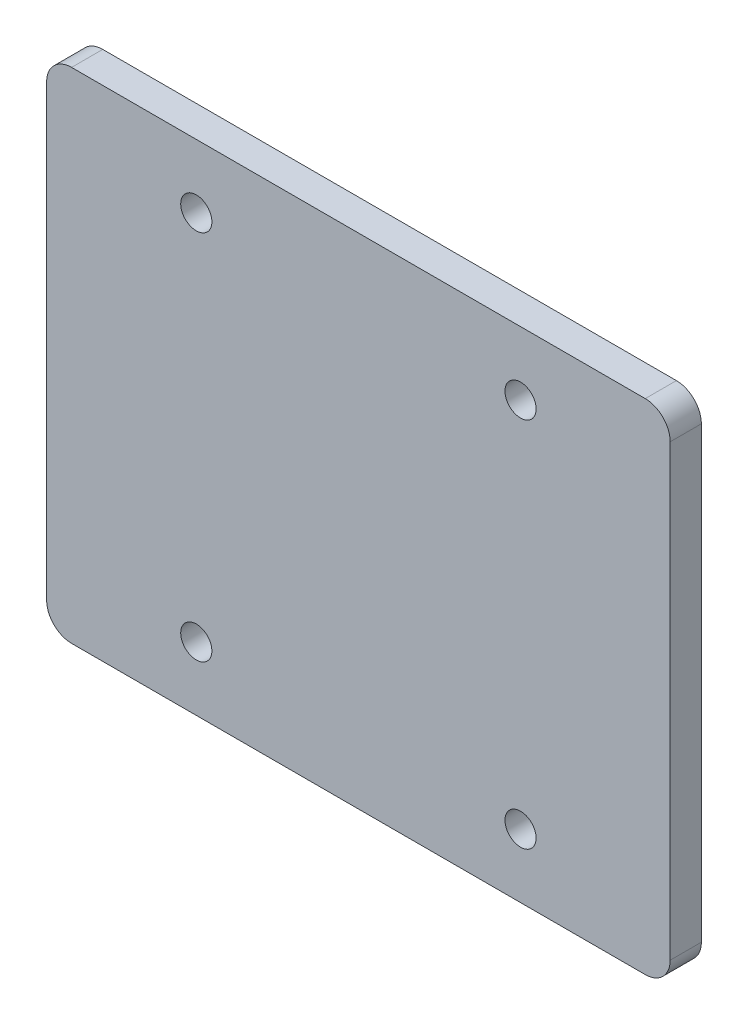
SolidWorks part; units mm, degrees
material "1060 Alloy"
ref_plane "Front Plane" through (0, 0, 0) normal (0, 0, 1) x (1, 0, 0)
ref_plane "Top Plane" through (0, 0, 0) normal (0, 1, 0) x (1, 0, 0)
ref_plane "Right Plane" through (0, 0, 0) normal (1, 0, 0) x (0, 0, -1)
sketch "Sketch1" plane through (0, 0, 0) normal (0, 0, 1) x (1, 0, 0)
  line L1 (0, 0) -> (63.5, 0)
  line L2 (0, 0) -> (0, 50.8)
  line L3 (0, 50.8) -> (63.5, 50.8)
  line L4 (63.5, 0) -> (63.5, 50.8)
  dimension "D1" = 63.5
  dimension "D2" = 50.8
extrude "Boss-Extrude1" add sketch "Sketch1" along normal blind 3.175
fillet "Fillet1" radius 2.54 4 edges at (0, 0, 1.5875) (63.5, 0, 1.5875) (0, 50.8, 1.5875) (63.5, 50.8, 1.5875)
sketch "Sketch2" plane through (0, 0, 3.175) normal (0, 0, 1) x (1, 0, 0)
  line L0 (31.75, 0) -> (31.75, 50.8)
  line L1 (2.54, 0) -> (60.96, 0) construction
  line L2 (60.96, 50.8) -> (2.54, 50.8) construction
  line L3 (63.5, 25.4) -> (0, 25.4)
  line L4 (63.5, 2.54) -> (63.5, 48.26) construction
  line L5 (0, 48.26) -> (0, 2.54) construction
sketch "Sketch3" plane through (0, 0, 0) normal (0, 0, -1) x (-1, 0, 0)
  line L0 (0, 25.4) -> (-63.5, 25.4)
  line L1 (0, 48.26) -> (0, 2.54) construction
  line L2 (-63.5, 2.54) -> (-63.5, 48.26) construction
  line L3 (-31.75, 0) -> (-31.75, 50.8)
  line L4 (-2.54, 0) -> (-60.96, 0) construction
  line L5 (-60.96, 50.8) -> (-2.54, 50.8) construction
sketch "Sketch4" plane through (0, 0, 3.175) normal (0, 0, 1) x (1, 0, 0)
  line L0 (2.54, 0) -> (60.96, 0) construction
  line L1 (0, 48.26) -> (0, 2.54) construction
  line L2 (63.5, 25.4) -> (0, 25.4) construction
  line L3 (63.5, 2.54) -> (63.5, 48.26) construction
  line L4 (31.75, 0) -> (31.75, 50.8) construction
  line L5 (60.96, 50.8) -> (2.54, 50.8) construction
  circle A0 centre (15.24, 6.477) radius 1.5875
  circle A1 centre (15.24, 44.323) radius 1.5875
  circle A2 centre (48.26, 44.323) radius 1.5875
  circle A3 centre (48.26, 6.477) radius 1.5875
  dimension "D1" = 3.175
  dimension "D2" = 6.477
  dimension "D3" = 15.24
extrude "Cut-Extrude1" cut sketch "Sketch4" against normal up to next (3.175 mm away) from surface at 0 starting at face at (31.75, 25.4, 3.175)
